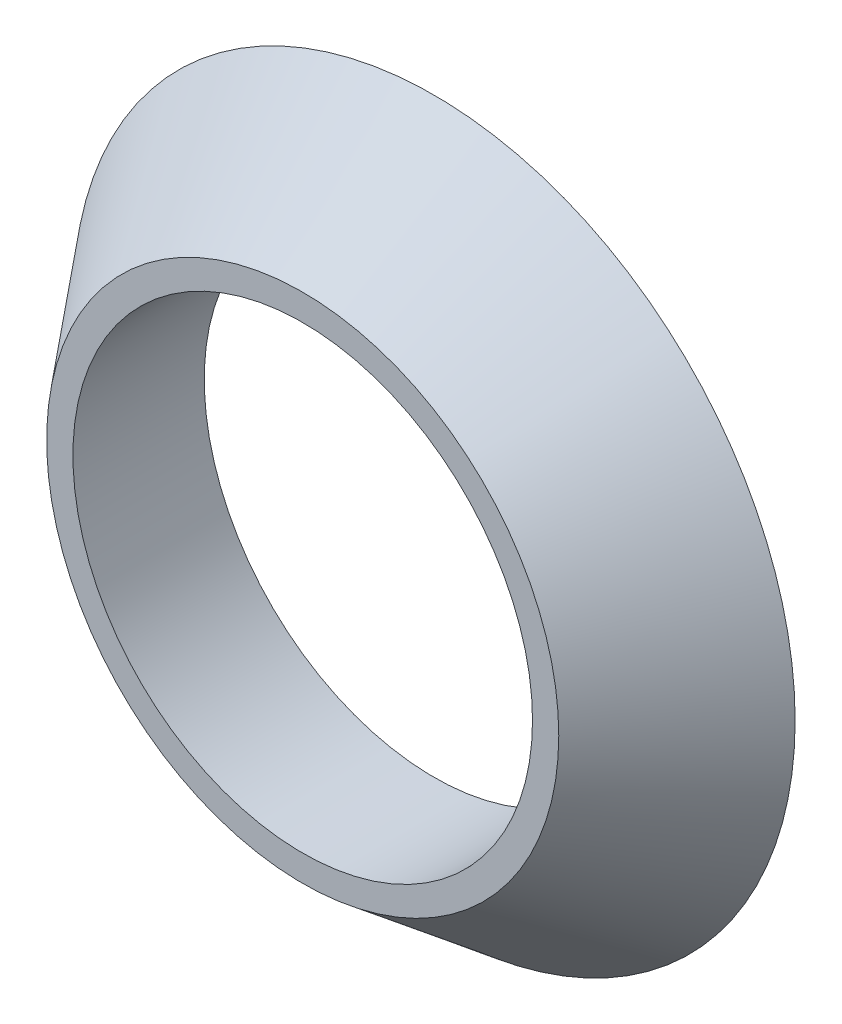
SolidWorks part; units mm, degrees
ref_plane "Front Plane" through (0, 0, 0) normal (0, 0, 1) x (1, 0, 0)
ref_plane "Top Plane" through (0, 0, 0) normal (0, 1, 0) x (1, 0, 0)
ref_plane "Right Plane" through (0, 0, 0) normal (1, 0, 0) x (0, 0, -1)
sketch "Sketch1" plane through (0, 0, 0) normal (1, 0, 0) x (0, 0, -1)
  line L0 (0, 0) -> (57.6616, 0) construction
  line L1 (26.1275, 22.225) -> (38.8275, 22.225)
  line L2 (38.8275, 22.225) -> (38.8275, 34.925)
  line L3 (38.8275, 34.925) -> (26.1275, 24.765)
  line L4 (26.1275, 24.765) -> (26.1275, 22.225)
  dimension "D1" = 22.225
  dimension "D2" = 12.7
  dimension "D3" = 2.54
  dimension "D4" = 12.7
revolve "Revolve1" add sketch "Sketch1" angle 360 about L0
